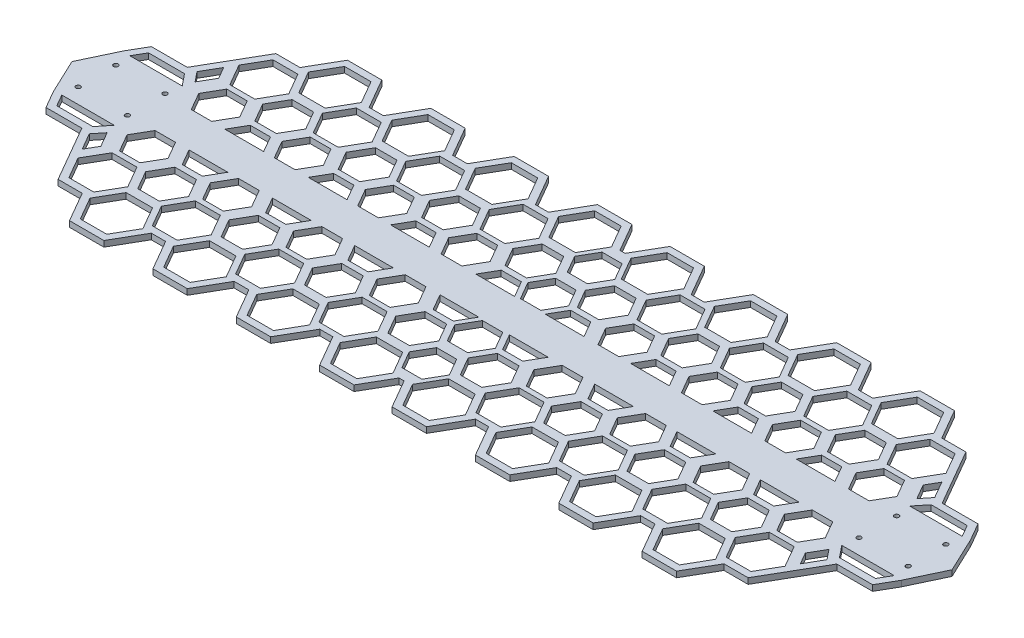
SolidWorks part; units mm, degrees
material "6061 Alloy"
ref_plane "Front Plane" through (0, 0, 0) normal (0, 0, 1) x (1, 0, 0)
ref_plane "Top Plane" through (0, 0, 0) normal (0, 1, 0) x (1, 0, 0)
ref_plane "Right Plane" through (0, 0, 0) normal (1, 0, 0) x (0, 0, -1)
sketch "Sketch2" plane through (0, 0, 0) normal (0, 1, 0) x (1, 0, 0)
  line L1 (-482.6, -152.4) -> (482.6, -152.4)
  line L2 (-482.6, -152.4) -> (-482.6, 152.4)
  line L3 (-482.6, 152.4) -> (482.6, 152.4)
  line L4 (482.6, -152.4) -> (482.6, 152.4)
  line L5 (-482.6, -152.4) -> (482.6, 152.4) construction
  line L6 (-482.6, 152.4) -> (482.6, -152.4) construction
  point P0 (0, 0)
  dimension "D1" = 304.8
  dimension "D2" = 965.2
extrude "Boss-Extrude1" add sketch "Sketch2" along normal blind 6.35
sketch "Sketch7" plane through (0, 6.35, 0) normal (0, 1, 0) x (1, 0, 0)
  line L166 (0, 0) -> (-401.7449, 0) construction
  line L221 (-16.1001, 64.2057) -> (-27.8978, 84.6399)
  line L222 (-27.8978, 84.6399) -> (-51.4931, 84.6399)
  line L223 (-51.4931, 84.6399) -> (-63.2908, 64.2057)
  line L224 (-63.2908, 64.2057) -> (-51.4931, 43.7716)
  line L225 (-51.4931, 43.7716) -> (-27.8978, 43.7716)
  line L226 (-27.8978, 43.7716) -> (-16.1001, 64.2057)
  line L227 (-10.6981, 119.7777) -> (-25.1968, 144.8901)
  line L228 (-25.1968, 144.8901) -> (-54.1941, 144.8901)
  line L229 (-54.1941, 144.8901) -> (-68.6928, 119.7777)
  line L230 (-68.6928, 119.7777) -> (-54.1941, 94.6652)
  line L231 (-54.1941, 94.6652) -> (-25.1968, 94.6652)
  line L232 (-25.1968, 94.6652) -> (-10.6981, 119.7777)
  line L233 (-63.3425, 39.3283) -> (-74.6979, 58.9962)
  line L234 (-74.6979, 58.9962) -> (-97.4085, 58.9962)
  line L235 (-97.4085, 58.9962) -> (-108.7638, 39.3283)
  line L236 (-108.7638, 39.3283) -> (-97.4085, 19.6603)
  line L237 (-97.4085, 19.6603) -> (-74.6979, 19.6603)
  line L238 (-74.6979, 19.6603) -> (-63.3425, 39.3283)
  line L239 (-58.7454, 88.2604) -> (-72.3993, 111.9096)
  line L240 (-72.3993, 111.9096) -> (-99.707, 111.9096)
  line L241 (-99.707, 111.9096) -> (-113.3609, 88.2604)
  line L242 (-113.3609, 88.2604) -> (-99.707, 64.6112)
  line L243 (-99.707, 64.6112) -> (-72.3993, 64.6112)
  line L244 (-72.3993, 64.6112) -> (-58.7454, 88.2604)
  line L257 (-107.5401, 64.2057) -> (-119.3378, 84.6399)
  line L258 (-119.3378, 84.6399) -> (-142.9331, 84.6399)
  line L259 (-142.9331, 84.6399) -> (-154.7308, 64.2057)
  line L260 (-154.7308, 64.2057) -> (-142.9331, 43.7716)
  line L261 (-142.9331, 43.7716) -> (-119.3378, 43.7716)
  line L262 (-119.3378, 43.7716) -> (-107.5401, 64.2057)
  line L263 (-102.1381, 119.7777) -> (-116.6368, 144.8901)
  line L264 (-116.6368, 144.8901) -> (-145.6341, 144.8901)
  line L265 (-145.6341, 144.8901) -> (-160.1328, 119.7777)
  line L266 (-160.1328, 119.7777) -> (-145.6341, 94.6652)
  line L267 (-145.6341, 94.6652) -> (-116.6368, 94.6652)
  line L268 (-116.6368, 94.6652) -> (-102.1381, 119.7777)
  line L269 (-154.7825, 39.3283) -> (-166.1379, 58.9962)
  line L270 (-166.1379, 58.9962) -> (-188.8485, 58.9962)
  line L271 (-188.8485, 58.9962) -> (-200.2038, 39.3283)
  line L272 (-200.2038, 39.3283) -> (-188.8485, 19.6603)
  line L273 (-188.8485, 19.6603) -> (-166.1379, 19.6603)
  line L274 (-166.1379, 19.6603) -> (-154.7825, 39.3283)
  line L275 (-150.1854, 88.2604) -> (-163.8393, 111.9096)
  line L276 (-163.8393, 111.9096) -> (-191.147, 111.9096)
  line L277 (-191.147, 111.9096) -> (-204.8009, 88.2604)
  line L278 (-204.8009, 88.2604) -> (-191.147, 64.6112)
  line L279 (-191.147, 64.6112) -> (-163.8393, 64.6112)
  line L280 (-163.8393, 64.6112) -> (-150.1854, 88.2604)
  line L293 (-198.9801, 64.2057) -> (-210.7778, 84.6399)
  line L294 (-210.7778, 84.6399) -> (-234.3731, 84.6399)
  line L295 (-234.3731, 84.6399) -> (-246.1708, 64.2057)
  line L296 (-246.1708, 64.2057) -> (-234.3731, 43.7716)
  line L297 (-234.3731, 43.7716) -> (-210.7778, 43.7716)
  line L298 (-210.7778, 43.7716) -> (-198.9801, 64.2057)
  line L299 (-193.5781, 119.7777) -> (-208.0768, 144.8901)
  line L300 (-208.0768, 144.8901) -> (-237.0741, 144.8901)
  line L301 (-237.0741, 144.8901) -> (-251.5728, 119.7777)
  line L302 (-251.5728, 119.7777) -> (-237.0741, 94.6652)
  line L303 (-237.0741, 94.6652) -> (-208.0768, 94.6652)
  line L304 (-208.0768, 94.6652) -> (-193.5781, 119.7777)
  line L305 (-246.2225, 39.3283) -> (-257.5779, 58.9962)
  line L306 (-257.5779, 58.9962) -> (-280.2885, 58.9962)
  line L307 (-280.2885, 58.9962) -> (-291.6438, 39.3283)
  line L308 (-291.6438, 39.3283) -> (-280.2885, 19.6603)
  line L309 (-280.2885, 19.6603) -> (-257.5779, 19.6603)
  line L310 (-257.5779, 19.6603) -> (-246.2225, 39.3283)
  line L311 (-241.6254, 88.2604) -> (-255.2793, 111.9096)
  line L312 (-255.2793, 111.9096) -> (-282.587, 111.9096)
  line L313 (-282.587, 111.9096) -> (-296.2409, 88.2604)
  line L314 (-296.2409, 88.2604) -> (-282.587, 64.6112)
  line L315 (-282.587, 64.6112) -> (-255.2793, 64.6112)
  line L316 (-255.2793, 64.6112) -> (-241.6254, 88.2604)
  line L329 (-290.4201, 64.2057) -> (-302.2178, 84.6399)
  line L330 (-302.2178, 84.6399) -> (-325.8131, 84.6399)
  line L331 (-325.8131, 84.6399) -> (-337.6108, 64.2057)
  line L332 (-337.6108, 64.2057) -> (-325.8131, 43.7716)
  line L333 (-325.8131, 43.7716) -> (-302.2178, 43.7716)
  line L334 (-302.2178, 43.7716) -> (-290.4201, 64.2057)
  line L335 (-285.0181, 119.7777) -> (-299.5168, 144.8901)
  line L336 (-299.5168, 144.8901) -> (-328.5141, 144.8901)
  line L337 (-328.5141, 144.8901) -> (-343.0128, 119.7777)
  line L338 (-343.0128, 119.7777) -> (-328.5141, 94.6652)
  line L339 (-328.5141, 94.6652) -> (-299.5168, 94.6652)
  line L340 (-299.5168, 94.6652) -> (-285.0181, 119.7777)
  line L347 (-333.0654, 88.2604) -> (-346.7193, 111.9096)
  line L348 (-346.7193, 111.9096) -> (-374.027, 111.9096)
  line L349 (-374.027, 111.9096) -> (-387.6809, 88.2604)
  line L350 (-387.6809, 88.2604) -> (-374.027, 64.6112)
  line L351 (-374.027, 64.6112) -> (-346.7193, 64.6112)
  line L352 (-346.7193, 64.6112) -> (-333.0654, 88.2604)
  line L359 (-337.6625, 39.3283) -> (-349.0179, 58.9962) [skipped]
  line L360 (-349.0179, 58.9962) -> (-371.7285, 58.9962) [skipped]
  line L361 (-371.7285, 58.9962) -> (-383.0838, 39.3283) [skipped]
  line L362 (-383.0838, 39.3283) -> (-371.7285, 19.6603) [skipped]
  line L363 (-371.7285, 19.6603) -> (-349.0179, 19.6603) [skipped]
  line L364 (-349.0179, 19.6603) -> (-337.6625, 39.3283) [skipped]
  line L377 (-393.7854, 77.5885) -> (-404.4943, 59.0402)
  line L396 (-337.9205, 39.3283) -> (-349.1468, 58.7729)
  line L397 (-349.1468, 58.7729) -> (-371.5995, 58.7729)
  line L398 (-371.5995, 58.7729) -> (-382.8259, 39.3283)
  line L399 (-382.8259, 39.3283) -> (-371.5995, 19.8837)
  line L400 (-371.5995, 19.8837) -> (-349.1468, 19.8837)
  line L401 (-349.1468, 19.8837) -> (-337.9205, 39.3283)
  line L402 (-404.4943, 59.0402) -> (-395.7516, 48.2201)
  line L403 (-395.7516, 48.2201) -> (-386.2905, 64.6071)
  line L404 (-386.2905, 64.6071) -> (-393.7854, 77.5885)
  line L405 (-409.4083, 50.2764) -> (-448.9091, 50.2764)
  line L406 (-448.9091, 50.2764) -> (-456.3986, 37.3042)
  line L407 (-456.3986, 37.3042) -> (-398.9267, 37.3042)
  line L408 (-398.9267, 37.3042) -> (-409.4083, 50.2764)
  line L409 (-387.6809, 88.2604) -> (-409.4083, 50.2764) construction
  line L416 (-232.8605, 37.3042) -> (-210.7471, 37.3042)
  line L417 (-324.3311, 37.3042) -> (-302.2178, 37.3042)
  line L418 (-302.2178, 37.3042) -> (-292.0311, 19.6603)
  line L419 (-292.0311, 19.6603) -> (-334.5179, 19.6603)
  line L420 (-334.5179, 19.6603) -> (-324.3311, 37.3042)
  line L439 (-210.7471, 37.3042) -> (-200.5604, 19.6603)
  line L440 (-200.5604, 19.6603) -> (-243.0472, 19.6603)
  line L441 (-243.0472, 19.6603) -> (-232.8605, 37.3042)
  line L442 (-142.6679, 37.3042) -> (-120.5545, 37.3042)
  line L443 (-120.5545, 37.3042) -> (-110.3678, 19.6603)
  line L444 (-110.3678, 19.6603) -> (-152.8546, 19.6603)
  line L445 (-152.8546, 19.6603) -> (-142.6679, 37.3042)
  line L446 (-49.1319, 37.3042) -> (-27.0186, 37.3042)
  line L447 (-27.0186, 37.3042) -> (-16.8319, 19.6603)
  line L448 (-16.8319, 19.6603) -> (-59.3187, 19.6603)
  line L449 (-59.3187, 19.6603) -> (-49.1319, 37.3042)
  circle A2 centre (-39.6954, 64.2057) radius 20.4341 construction
  circle A3 centre (-39.6954, 119.7777) radius 25.1125 construction
  circle A4 centre (-86.0532, 39.3283) radius 19.668 construction
  circle A5 centre (-86.0532, 88.2604) radius 23.6492 construction
  circle A8 centre (-131.1354, 64.2057) radius 20.4341 construction
  circle A9 centre (-131.1354, 119.7777) radius 25.1125 construction
  circle A10 centre (-177.4932, 39.3283) radius 19.668 construction
  circle A11 centre (-177.4932, 88.2604) radius 23.6492 construction
  circle A14 centre (-222.5754, 64.2057) radius 20.4341 construction
  circle A15 centre (-222.5754, 119.7777) radius 25.1125 construction
  circle A16 centre (-268.9332, 39.3283) radius 19.668 construction
  circle A17 centre (-268.9332, 88.2604) radius 23.6492 construction
  circle A19 centre (-360.3732, 39.3283) radius 19.4446 construction
  circle A20 centre (-314.0154, 64.2057) radius 20.4341 construction
  circle A21 centre (-314.0154, 119.7777) radius 25.1125 construction
  circle A23 centre (-360.3732, 88.2604) radius 23.6492 construction
  circle A25 centre (-360.3732, 39.3283) radius 19.668 construction
  point P181 (0, 0)
  dimension "D1" = 2
  dimension "D2" = 2
extrude "Cut-Extrude3" cut sketch "Sketch7" against normal through all
sketch "Sketch3" plane through (0, 6.35, 0) normal (0, 1, 0) x (1, 0, 0)
  line L0 (0, 0) -> (-890.435, 0) construction
  line L1 (0, 0) -> (901.0118, 0) construction
  line L2 (0, 0) -> (0, 150.6469) construction
  line L3 (0, 0) -> (0, -245.2497) construction
  line L4 (-482.6, 0) -> (-464.776, 37.6314)
  line L9 (-20.8609, 152.4) -> (-2.8236, 121.1584)
  line L16 (-482.6, 0) -> (-689.3836, 0)
  line L17 (-689.3836, 0) -> (-689.3836, 240.3533)
  line L18 (-689.3836, 240.3533) -> (-11.7344, 240.3533)
  line L20 (-482.6, 152.4) -> (-482.6, -152.4) construction
  line L22 (482.6, 152.4) -> (-482.6, 152.4) construction
  line L23 (-20.8609, 152.4) -> (-58.53, 152.4)
  line L24 (-58.53, 152.4) -> (-78.2518, 118.2408)
  line L25 (-78.2518, 118.2408) -> (-92.5791, 118.2408)
  line L26 (-92.5791, 118.2408) -> (-112.3009, 152.4)
  line L27 (-112.3009, 152.4) -> (-149.97, 152.4)
  line L28 (-149.97, 152.4) -> (-168.8045, 119.7777)
  line L29 (-168.8045, 119.7777) -> (-184.9064, 119.7777)
  line L30 (-184.9064, 119.7777) -> (-203.7409, 152.4)
  line L31 (-203.7409, 152.4) -> (-241.41, 152.4)
  line L32 (-241.41, 152.4) -> (-260.4513, 119.4194)
  line L33 (-260.4513, 119.4194) -> (-276.1396, 119.4194)
  line L34 (-276.1396, 119.4194) -> (-295.1809, 152.4)
  line L35 (-295.1809, 152.4) -> (-332.85, 152.4)
  line L36 (-332.85, 152.4) -> (-351.8913, 119.4194)
  line L37 (-351.8913, 119.4194) -> (-378.3629, 119.4194)
  line L38 (-378.3629, 119.4194) -> (-395.6465, 89.4834)
  line L39 (-328.5141, 144.8901) -> (-343.0128, 119.7777) construction
  line L40 (-374.027, 111.9096) -> (-387.6809, 88.2604) construction
  line L44 (-387.6809, 88.2604) -> (-374.027, 64.6112) construction
  line L45 (-378.7378, 103.7502) -> (-385.2416, 107.5052) construction
  line L46 (-381.5581, 55.1457) -> (-375.0544, 51.3907) construction
  line L47 (-2.8236, 121.1584) -> (0, 121.1584)
  line L48 (-10.6981, 119.7777) -> (-25.1968, 144.8901) construction
  line L49 (-102.1381, 119.7777) -> (-116.6368, 144.8901) construction
  line L50 (-54.1941, 144.8901) -> (-68.6928, 119.7777) construction
  line L51 (-72.3993, 111.9096) -> (-99.707, 111.9096) construction
  line L52 (-193.5781, 119.7777) -> (-208.0768, 144.8901) construction
  line L53 (-163.8393, 111.9096) -> (-191.147, 111.9096) construction
  line L54 (-145.6341, 144.8901) -> (-160.1328, 119.7777) construction
  line L56 (-25.1968, 144.8901) -> (-54.1941, 144.8901) construction
  line L57 (-39.6954, 144.8901) -> (-39.6954, 152.4) construction
  line L58 (-85.4154, 110.7309) -> (-85.4154, 118.2408) construction
  line L59 (-100.8822, 132.6222) -> (-107.3859, 128.8673) construction
  line L60 (-160.0362, 134.9647) -> (-153.5325, 131.2098) construction
  line L61 (-176.8554, 112.2678) -> (-176.8554, 119.7777) construction
  line L62 (-200.8274, 132.3339) -> (-194.3237, 136.0888) construction
  line L63 (-244.3235, 132.3339) -> (-250.8272, 136.0888) construction
  line L64 (-237.0741, 144.8901) -> (-251.5728, 119.7777) construction
  line L65 (-70.2675, 132.0699) -> (-63.7638, 128.315) construction
  line L66 (-264.0557, 111.9096) -> (-264.0557, 119.4194) construction
  line L67 (-255.2793, 111.9096) -> (-282.587, 111.9096) construction
  line L68 (-295.727, 138.326) -> (-289.2232, 142.0809) construction
  line L69 (-285.0181, 119.7777) -> (-299.5168, 144.8901) construction
  line L70 (-332.3039, 138.326) -> (-338.8077, 142.0809) construction
  line L71 (-346.7193, 111.9096) -> (-374.027, 111.9096) construction
  line L72 (-358.3286, 111.9096) -> (-358.3286, 119.4194) construction
  line L73 (-392.2446, 83.5912) -> (-386.8, 86.7347) construction
  line L75 (0, 121.1584) -> (0, 240.3533)
  line L76 (0, 240.3533) -> (-11.7344, 240.3533)
  line L78 (-464.776, 37.6314) -> (-464.8813, 37.6314)
  line L79 (-464.8813, 37.6314) -> (-453.2449, 57.7863)
  line L80 (-453.2449, 57.7863) -> (-413.9468, 57.7863)
  line L81 (-413.9468, 57.7863) -> (-395.6465, 89.4834)
  line L82 (-424.2438, 57.7863) -> (-424.2438, 50.2764) construction
  line L83 (-409.4083, 50.2764) -> (-448.9091, 50.2764) construction
  line L84 (-448.6822, 50.6694) -> (-455.186, 54.4243) construction
  line L85 (-448.9091, 50.2764) -> (-456.3986, 37.3042) construction
  line L86 (-393.7854, 77.5885) -> (-404.4943, 59.0402) construction
  dimension "D1" = 64.656
sketch "Sketch8" plane through (0, 6.35, 0) normal (0, 1, 0) x (1, 0, 0)
  line L1 (10.9945, 109.7378) -> (-10.9945, 109.7378)
  line L2 (-10.9945, 109.7378) -> (-21.989, 90.6948)
  line L3 (-21.989, 90.6948) -> (-10.9945, 71.6518)
  line L4 (-10.9945, 71.6518) -> (10.9945, 71.6518)
  line L5 (10.9945, 71.6518) -> (21.989, 90.6948)
  line L6 (21.989, 90.6948) -> (10.9945, 109.7378)
  line L7 (10.7289, 59.45) -> (-11.5565, 59.45)
  line L8 (-11.5565, 59.45) -> (-22.6991, 40.1504)
  line L9 (-22.6991, 40.1504) -> (-11.5565, 20.8507)
  line L10 (-11.5565, 20.8507) -> (10.7289, 20.8507)
  line L11 (10.7289, 20.8507) -> (21.8715, 40.1504)
  line L12 (21.8715, 40.1504) -> (10.7289, 59.45)
  circle A0 centre (0, 90.6948) radius 19.043 construction
  circle A1 centre (-0.4138, 40.1504) radius 19.2996 construction
  point P17 (0, 0)
extrude "Cut-Extrude4" cut sketch "Sketch8" against normal through all
extrude "Cut-Extrude5" cut sketch "Sketch3" against normal through all contours L76 L18 L17 L16 L4 L78 L79 L80 L81 L38 L37 L36 L35 L34 L33 L32 L31 L30 L29 L28 L27 L26 L25 L24 L23 L9 L47 L75
fillet "Fillet1" [suppressed] radius 2.38
mirror "Mirror10" about plane through (0, 0, 0) normal (1, 0, 0) of "Cut-Extrude3", "Cut-Extrude5"
mirror "Mirror11" about plane through (0, 0, 0) normal (0, 0, 1) of "Cut-Extrude4", "Mirror10", "Cut-Extrude3", "Cut-Extrude5"
hole_wizard "#10 (0.1935) Diameter Hole2" positions "Sketch11" profile "Sketch10" hole size "#10" standard "ANSI Inch" end condition through all
sketch "Sketch11" plane through (0, 6.35, 0) normal (0, 1, 0) x (1, 0, 0)
  line L0 (-455.1274, 0) -> (-455.1274, 20.6375) construction
  line L2 (-455.1274, 0) -> (-455.1274, -20.6375) construction
  line L4 (-455.1274, 20.6375) -> (-401.1524, 20.6375) construction
  line L6 (-401.1524, 20.6375) -> (-401.1524, -20.6375) construction
  point P2 (-455.1274, 20.6375)
  point P7 (-455.1274, -20.6375)
  point P12 (-401.1524, 20.6375)
  point P17 (-401.1524, -20.6375)
  dimension "D1" = 20.6375
  dimension "D2" = 20.6375
  dimension "D3" = 53.975
sketch "Sketch10" plane through (-401.1524, 6.35, 20.6375) normal (1, 0, 0) x (0, 0, 1)
  line L0 (0, 0) -> (0, 6.35)
  line L1 (0, 6.35) -> (2.4574, 6.35)
  line L2 (2.4574, 6.35) -> (2.4574, 0)
  line L5 (2.4574, 0) -> (0, 0)
  line L11 (0, -6.35) -> (0, 107.95) construction
  dimension "Thru Hole Dia." = 4.9149
  dimension "Thru Hole Depth" = 6.35
mirror "Mirror12" about plane through (0, 0, 0) normal (1, 0, 0) of "#10 (0.1935) Diameter Hole2"
